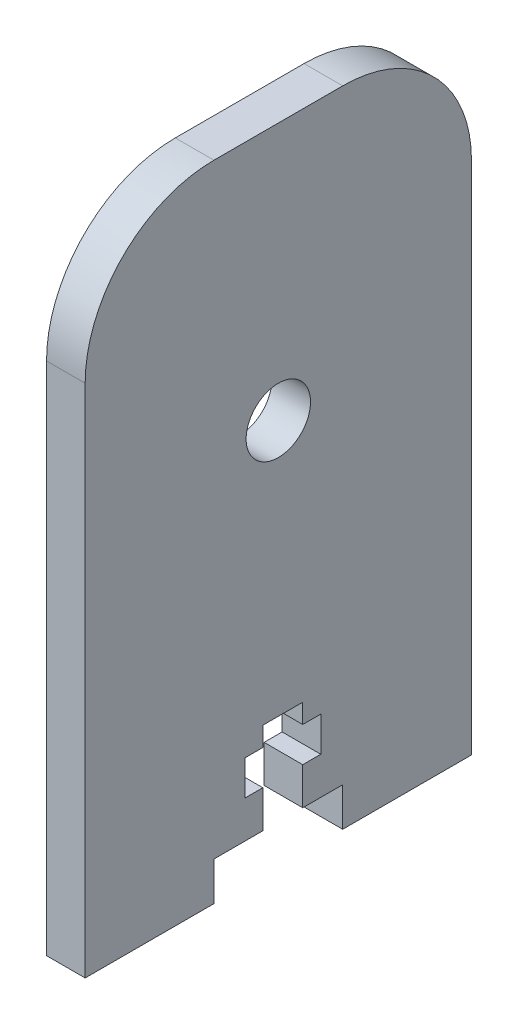
SolidWorks part; units mm, degrees
ref_plane "Front Plane" through (0, 0, 0) normal (0, 0, 1) x (1, 0, 0)
ref_plane "Top Plane" through (0, 0, 0) normal (0, 1, 0) x (1, 0, 0)
ref_plane "Right Plane" through (0, 0, 0) normal (1, 0, 0) x (0, 0, -1)
sketch "Sketch1" plane through (0, 0, 0) normal (1, 0, 0) x (0, 0, -1)
  line L1 (0, 0) -> (30, 0)
  line L2 (0, 0) -> (0, 50)
  line L3 (0, 50) -> (30, 50)
  line L4 (30, 0) -> (30, 50)
  dimension "D1" = 30
  dimension "D2" = 50
extrude "Boss-Extrude1" add sketch "Sketch1" along normal blind 3
fillet "Fillet1" radius 10 2 edges at (1.5, 50, -30) (1.5, 50, 0)
sketch "Sketch2" plane through (3, 0, 0) normal (1, 0, 0) x (0, 0, -1)
  line L0 (0, 0) -> (30, 0) construction
  line L1 (10, 0) -> (20, 0)
  line L2 (10, 0) -> (10, 3)
  line L3 (10, 3) -> (20, 3)
  line L4 (20, 0) -> (20, 3)
  line L5 (0, 40) -> (0, 0) construction
  dimension "D1" = 3
  dimension "D2" = 10
  dimension "D3" = 10
extrude "Cut-Extrude1" cut sketch "Sketch2" against normal blind 3
hole_wizard "Ø5.0mm Dowel Hole1" positions "Sketch3" profile "Sketch4" hole size "Ø5.0" standard "ANSI Metric"
sketch "Sketch3" plane through (3, 0, 0) normal (1, 0, 0) x (0, 0, -1)
  line L0 (0, 0) -> (10, 0) construction
  line L1 (0, 40) -> (0, 0) construction
  point P0 (15, 30)
  dimension "D1" = 30
  dimension "D2" = 15
sketch "Sketch4" plane through (3, 30, -15) normal (0, 1, 0) x (0, 0, -1)
  line L0 (0, 0) -> (0, 4.5022)
  line L1 (0, 4.5022) -> (2.5, 3)
  line L2 (2.5, 3) -> (2.5, 0)
  line L5 (2.5, 0) -> (0, 0)
  line L10 (0, 4.5022) -> (-2.5, 3) construction
  line L11 (0, -6.35) -> (0, 107.95) construction
  dimension "Hole Dia." = 5
  dimension "Hole Depth" = 3
  dimension "Drill Angle" = 118
sketch "Sketch5" plane through (3, 0, 0) normal (1, 0, 0) x (0, 0, -1)
  line L0 (13.7962, 3) -> (13.7962, 5.9)
  line L1 (20, 3) -> (10, 3) construction
  line L2 (13.7962, 5.9) -> (12.3962, 5.9)
  line L3 (12.3962, 5.9) -> (12.3962, 8.6)
  line L4 (12.3962, 8.6) -> (13.7962, 8.6)
  line L5 (13.7962, 8.6) -> (13.7962, 10.1)
  line L6 (13.7962, 10.1) -> (16.8962, 10.1)
  line L7 (16.8962, 10.1) -> (16.8962, 8.6)
  line L8 (16.8962, 8.6) -> (18.2962, 8.6)
  line L9 (18.2962, 8.6) -> (18.2962, 5.9)
  line L10 (18.2962, 5.9) -> (16.8962, 5.9)
  line L11 (16.8962, 5.9) -> (16.8962, 3)
  line L12 (16.8962, 3) -> (13.7962, 3)
  line L13 (0, 0) -> (10, 0) construction
  dimension "D1" = 3.1
  dimension "D2" = 5.9
  dimension "D3" = 1.5
  dimension "D4" = 2.7
  dimension "D5" = 10.1
extrude "Cut-Extrude2" cut sketch "Sketch5" against normal blind 3
